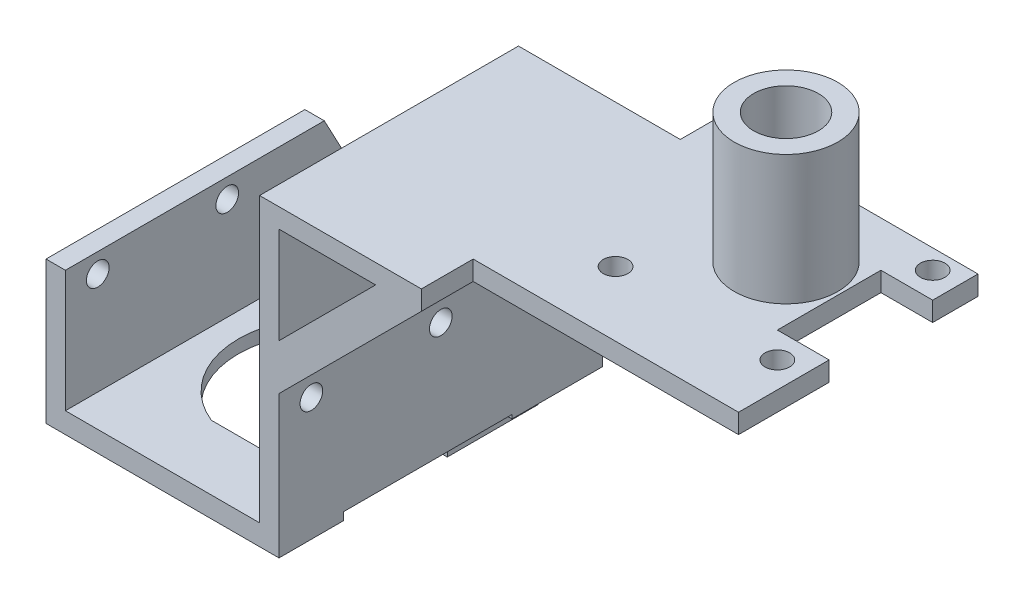
SolidWorks part; units mm, degrees
material "1060 合金"
ref_plane "前视基准面" through (0, 0, 0) normal (0, 0, 1) x (1, 0, 0)
ref_plane "上视基准面" through (0, 0, 0) normal (0, 1, 0) x (1, 0, 0)
ref_plane "右视基准面" through (0, 0, 0) normal (1, 0, 0) x (0, 0, -1)
sketch "草图1" plane through (0, 0, 0) normal (0, 1, 0) x (1, 0, 0)
  line L1 (-18, 20) -> (18, 20)
  line L2 (-18, 20) -> (-18, -20)
  line L3 (-18, -20) -> (18, -20)
  line L4 (18, 20) -> (18, -20)
  line L5 (-18, 20) -> (18, -20) construction
  line L6 (-18, -20) -> (18, 20) construction
  point P0 (0, 0)
  dimension "D1" = 40
  dimension "D2" = 36
extrude "凸台-拉伸1" add sketch "草图1" along normal blind 3
ref_plane "基准面1" through (0, 3, 0) normal (0, 1, 0) x (1, 0, 0)
sketch "草图2" plane through (0, 3, 0) normal (0, 1, 0) x (1, 0, 0)
  line L0 (-18, -20) -> (18, -20) construction
  line L1 (-18, 20) -> (-15, 20)
  line L2 (-18, 20) -> (-18, -20)
  line L3 (-18, -20) -> (-15, -20)
  line L4 (-15, 20) -> (-15, -20)
  line L6 (18, 20) -> (15, 20)
  line L7 (18, 20) -> (18, -20)
  line L8 (18, -20) -> (15, -20)
  line L9 (15, 20) -> (15, -20)
  dimension "D1" = 3
  dimension "D2" = 3
extrude "凸台-拉伸2" add sketch "草图2" along normal blind 18.8
ref_plane "基准面2" through (0, 0, 0) normal (0, -1, 0) x (-1, 0, 0)
sketch "草图3" plane through (0, 0, 0) normal (0, -1, 0) x (-1, 0, 0)
  circle A0 centre (-2.75, 3) radius 14
  dimension "D1" = 28
extrude "切除-拉伸1" cut sketch "草图3" against normal blind 9
ref_plane "基准面3" through (0, 0, 20) normal (0, 0, 1) x (1, 0, 0)
sketch "草图4" plane through (0, 0, 20) normal (0, 0, 1) x (1, 0, 0)
  line L0 (18, 21.8) -> (18, 0) construction
  line L1 (-18, 0) -> (18, 0)
  line L2 (-18, 0) -> (-18, 3)
  line L3 (-18, 3) -> (18, 3)
  line L4 (18, 0) -> (18, 3)
  line L5 (16.5, 3) -> (-16.5, 3) construction
extrude "凸台-拉伸3" add sketch "草图4" along normal blind 10
sketch "草图6" plane through (0, 0, 0) normal (0, -1, 0) x (-1, 0, 0)
  circle A0 centre (-2.75, -16.15) radius 2.7
  dimension "D2" = 5.4
  dimension "D1" = 19.15
extrude "切除-拉伸3" cut sketch "草图6" against normal blind 10
ref_plane "基准面4" through (-18, 0, 0) normal (-1, 0, 0) x (0, 0, 1)
sketch "草图7" plane through (-18, 0, 0) normal (-1, 0, 0) x (0, 0, 1)
  line L0 (20, -1.65) -> (20, 1.65) construction
  line L2 (-20, 21.8) -> (20, 21.8) construction
  circle A0 centre (15, 18.8) radius 1.75
  circle A1 centre (-5, 18.8) radius 1.75
  dimension "D1" = 3.5
  dimension "D2" = 3.5
  dimension "D3" = 5
  dimension "D4" = 3
  dimension "D5" = 3
  dimension "D6" = 20
extrude "切除-拉伸4" cut sketch "草图7" against normal through all
ref_plane "基准面5" through (0, 0, 0) normal (0, -1, 0) x (-1, 0, 0)
ref_plane "基准面6" through (0, 0, 30) normal (0, 0, 1) x (1, 0, 0)
sketch "草图9" plane through (0, 0, 30) normal (0, 0, 1) x (1, 0, 0)
  line L0 (-18, 13.365) -> (-18, -13.365) construction
  line L1 (-18, 0) -> (-15, 0)
  line L2 (-18, 0) -> (-18, -9.3)
  line L3 (-18, -9.3) -> (-15, -9.3)
  line L4 (-15, 0) -> (-15, -9.3)
  line L5 (-18, 3) -> (-18, 0) construction
  line L6 (-55, 0) -> (55, 0) construction
  line L7 (-15, -9.3) -> (10, -9.3)
  line L8 (-15, -9.3) -> (-15, -6.3)
  line L9 (-15, -6.3) -> (10, -6.3)
  line L10 (10, -9.3) -> (10, -6.3)
  dimension "D1" = 3
  dimension "D2" = 9.3
  dimension "D3" = 3
  dimension "D4" = 25
extrude "凸台-拉伸4" add sketch "草图9" against normal blind 20 contours L7 L10 L9 L4 | L4 L1 L2 L3
chamfer "倒角1" distance 5 angle 45 1 edges at (10, -7.8, 30)
sketch "草图10" plane through (0, 0, 0) normal (0, 1, 0) x (1, 0, 0)
  circle A0 centre (2.75, -16.15) radius 2.7
extrude "切除-拉伸5" cut sketch "草图10" against normal blind 30
sketch "草图11" plane through (-18, 0, 0) normal (-1, 0, 0) x (0, 0, 1)
  line L1 (40.054, -18.0711) -> (0, -18.0711)
  line L2 (40.054, -18.0711) -> (40.054, 0)
  line L3 (40.054, 0) -> (0, 0)
  line L4 (0, -18.0711) -> (0, 0)
extrude "切除-拉伸6" cut sketch "草图11" against normal through all
sketch "草图12" plane through (0, 0, 0) normal (0, -1, 0) x (-1, 0, 0)
  line L0 (18, 20) -> (18, -30) construction
  line L1 (-18, -30) -> (18, -30)
  line L2 (-18, -30) -> (-18, -10)
  line L3 (-18, -10) -> (18, -10)
  line L4 (18, -30) -> (18, -10)
  circle A0 centre (-2.75, -16.15) radius 2.7
  dimension "D1" = 20
extrude "凸台-拉伸5" add sketch "草图12" along normal blind 2.5
sketch "草图13" plane through (0, 0, 0) normal (0, -1, 0) x (-1, 0, 0)
  line L1 (-30.9744, -10) -> (31.1483, -10)
  line L2 (-30.9744, -10) -> (-30.9744, 25.5614)
  line L3 (-30.9744, 25.5614) -> (31.1483, 25.5614)
  line L4 (31.1483, -10) -> (31.1483, 25.5614)
extrude "切除-拉伸7" cut sketch "草图13" against normal blind 1
ref_plane "基准面7" through (18, 0, 0) normal (1, 0, 0) x (0, 0, -1)
ref_plane "基准面8" through (0, 0, 20) normal (0, 0, 1) x (1, 0, 0)
sketch "草图16" plane through (0, 0, 20) normal (0, 0, 1) x (1, 0, 0)
  line L0 (18, -13.365) -> (18, 13.365) construction
  line L1 (15, 21.8) -> (18, 21.8)
  line L2 (15, 21.8) -> (15, 46.8)
  line L3 (15, 46.8) -> (18, 46.8)
  line L4 (18, 21.8) -> (18, 46.8)
  line L6 (18, 46.8) -> (78, 46.8)
  line L7 (18, 46.8) -> (18, 43.8)
  line L8 (18, 43.8) -> (78, 43.8)
  line L9 (78, 46.8) -> (78, 43.8)
  dimension "D1" = 25
  dimension "D2" = 60
  dimension "D3" = 3
extrude "凸台-拉伸7" add sketch "草图16" against normal blind 65 contours L9 L6 L4 L8 | L1 L4 L3 L2
ref_plane "基准面9" through (0, 9, 0) normal (0, -1, 0) x (-1, 0, 0)
sketch "草图17" plane through (0, 9, 0) normal (0, -1, 0) x (-1, 0, 0)
  line L0 (-15, 9.7777) -> (-15, -3.7777)
  circle A0 centre (-2.75, 3) radius 14
extrude "凸台-拉伸8" add sketch "草图17" along normal up to surface (8 mm away) contours L0 A0
ref_plane "基准面10" through (0, 46.8, 0) normal (0, 1, 0) x (1, 0, 0)
sketch "草图18" plane through (0, 46.8, 0) normal (0, 1, 0) x (1, 0, 0)
  line L0 (78, 45) -> (78, -20) construction
  line L1 (47.75, 25.75) -> (74.25, 25.75) construction
  line L2 (47.75, 25.75) -> (47.75, -0.75) construction
  line L3 (47.75, -0.75) -> (74.25, -0.75) construction
  line L4 (74.25, 25.75) -> (74.25, -0.75) construction
  line L5 (47.75, 25.75) -> (74.25, -0.75) construction
  line L6 (47.75, -0.75) -> (74.25, 25.75) construction
  line L10 (47.75, 12.5) -> (74.25, 12.5) construction
  line L11 (52, -0.75) -> (70, -0.75) construction
  line L12 (52, -2.75) -> (70, -2.75)
  line L13 (52, 1.25) -> (70, 1.25)
  line L14 (15, 12.5) -> (78, 12.5) construction
  line L15 (15, 45) -> (15, -20) construction
  circle A2 centre (74.25, -0.75) radius 1.15
  circle A3 centre (47.75, -0.75) radius 1.15
  circle A4 centre (61, 12.5) radius 10
  arc A7 (52, -2.75) -> (52, 1.25) centre (52, -0.75) cw
  arc A8 (70, 1.25) -> (70, -2.75) centre (70, -0.75) cw
  point P0 (61, 12.5)
  point P24 (61, -0.75)
  dimension "D3" = 13.25
  dimension "D4" = 2
  dimension "D5" = 2.3
  dimension "D6" = 2.3
  dimension "D8" = 20
  dimension "D1" = 26.5
  dimension "D2" = 26.5
  dimension "D7" = 17
  dimension "D9" = 18
ref_plane "基准面11" through (0, -2.5, 0) normal (0, -1, 0) x (-1, 0, 0)
sketch "草图19" plane through (0, -2.5, 0) normal (0, -1, 0) x (-1, 0, 0)
  line L1 (-57.3424, 35.7643) -> (67.8869, 35.7643)
  line L2 (-57.3424, 35.7643) -> (-57.3424, -68.1586)
  line L3 (-57.3424, -68.1586) -> (67.8869, -68.1586)
  line L4 (67.8869, 35.7643) -> (67.8869, -68.1586)
extrude "切除-拉伸9" cut sketch "草图19" against normal blind 0.5
ref_plane "基准面12" through (0, -2, 0) normal (0, -1, 0) x (-1, 0, 0)
sketch "草图20" plane through (0, -2, 0) normal (0, -1, 0) x (-1, 0, 0)
  line L1 (-74.5179, 37.5036) -> (80.2794, 37.5036)
  line L2 (-74.5179, 37.5036) -> (-74.5179, -52.9398)
  line L3 (-74.5179, -52.9398) -> (80.2794, -52.9398)
  line L4 (80.2794, 37.5036) -> (80.2794, -52.9398)
extrude "切除-拉伸10" cut sketch "草图20" against normal blind 1.8
ref_plane "基准面13" through (0, 0, 0) normal (0, 1, 0) x (1, 0, 0)
sketch "草图21" plane through (0, 0, 0) normal (0, 1, 0) x (1, 0, 0)
  line L1 (-2.4461, -10) -> (8.7096, -10)
  line L2 (-2.4461, -10) -> (-2.4461, -12.6038)
  line L3 (-2.4461, -12.6038) -> (8.7096, -12.6038)
  line L4 (8.7096, -10) -> (8.7096, -12.6038)
extrude "凸台-拉伸9" add sketch "草图21" along normal up to surface (3 mm away) up to face at (2.75, 3, 18.85)
ref_plane "基准面14" through (0, 0, -20) normal (0, 0, -1) x (-1, 0, 0)
sketch "草图22" plane through (0, 0, -20) normal (0, 0, -1) x (-1, 0, 0)
  line L0 (18, -17.325) -> (18, 17.325) construction
  line L1 (18, 3) -> (-18, 3)
  line L2 (18, 3) -> (18, -0.2)
  line L3 (18, -0.2) -> (-18, -0.2)
  line L4 (-18, 3) -> (-18, -0.2)
  line L5 (18, 3) -> (18, -0.2) construction
  line L6 (-18, 21.8) -> (-18, 1) construction
  line L7 (-15, 3) -> (15, 3) construction
  dimension "D1" = 3.2
extrude "凸台-拉伸10" add sketch "草图22" along normal blind 10 and the other way blind 4
sketch "草图23" plane through (0, 9, 0) normal (0, -1, 0) x (-1, 0, 0)
  circle A0 centre (-2.75, 22.15) radius 1.75
  arc A1 (2.4461, -10) -> (2.4462, 16) centre (-2.75, 3) ccw construction
  dimension "D1" = 19.15
  dimension "D2" = 3.5
extrude "切除-拉伸12" cut sketch "草图23" along normal blind 10
sketch "草图26" plane through (0, 3, 0) normal (0, 1, 0) x (1, 0, 0)
  line L1 (-3.0023, -13.2404) -> (9.8436, -13.2404)
  line L2 (-3.0023, -13.2404) -> (-3.0023, -20.6177)
  line L3 (-3.0023, -20.6177) -> (9.8436, -20.6177)
  line L4 (9.8436, -13.2404) -> (9.8436, -20.6177)
extrude "凸台-拉伸11" add sketch "草图26" against normal through all
sketch "草图27" plane through (0, 0, 30) normal (0, 0, 1) x (1, 0, 0)
  line L1 (-53.429, 28.6042) -> (62.9951, 28.6042)
  line L2 (-53.429, 28.6042) -> (-53.429, -33.9017)
  line L3 (-53.429, -33.9017) -> (62.9951, -33.9017)
  line L4 (62.9951, 28.6042) -> (62.9951, -33.9017)
extrude "切除-拉伸13" cut sketch "草图27" against normal blind 10
ref_plane "基准面16" through (0, 46.8, 0) normal (0, 1, 0) x (1, 0, 0)
sketch "草图29" plane through (0, 46.8, 0) normal (0, 1, 0) x (1, 0, 0)
  line L0 (-12.1, -20) -> (12.1, -20) construction
  line L1 (88.2149, 37) -> (-1.5762, 37)
  line L2 (88.2149, 37) -> (88.2149, 49.2847)
  line L3 (88.2149, 49.2847) -> (-1.5762, 49.2847)
  line L4 (-1.5762, 37) -> (-1.5762, 49.2847)
  line L5 (110.1735, -41.7854) -> (2.772, -41.7854)
  line L6 (110.1735, -41.7854) -> (110.1735, -12)
  line L7 (110.1735, -12) -> (2.772, -12)
  line L8 (2.772, -41.7854) -> (2.772, -12)
  line L9 (15, 45) -> (78, 45) construction
  dimension "D1" = 8
  dimension "D2" = 8
extrude "切除-拉伸14" cut sketch "草图29" against normal blind 25
ref_plane "基准面17" through (0, 0, -20) normal (0, 0, -1) x (-1, 0, 0)
sketch "草图30" plane through (0, 0, -20) normal (0, 0, -1) x (-1, 0, 0)
  line L0 (19.8, 3) -> (-19.8, 3) construction
  line L1 (-18, 21.8) -> (-15, 21.8)
  line L2 (-18, 21.8) -> (-18, 3)
  line L3 (-18, 3) -> (-15, 3)
  line L4 (-15, 21.8) -> (-15, 3)
  line L5 (18, 3) -> (-18, 3) construction
extrude "凸台-拉伸12" add sketch "草图30" along normal up to surface (17 mm away) up to face at (37, 37.4667, -37)
ref_plane "基准面18" through (0, -0.2, 0) normal (0, -1, 0) x (-1, 0, 0)
sketch "草图31" plane through (0, -0.2, 0) normal (0, -1, 0) x (-1, 0, 0)
  line L1 (-43.7541, 52.6137) -> (37.0144, 52.6137)
  line L2 (-43.7541, 52.6137) -> (-43.7541, 6.8485)
  line L3 (-43.7541, 6.8485) -> (37.0144, 6.8485)
  line L4 (37.0144, 52.6137) -> (37.0144, 6.8485)
extrude "切除-拉伸15" cut sketch "草图31" against normal blind 0.6
ref_plane "基准面19" through (0, 0, -30) normal (0, 0, -1) x (-1, 0, 0)
sketch "草图32" plane through (0, 0, -30) normal (0, 0, -1) x (-1, 0, 0)
  line L0 (15, 21.8) -> (15, 3) construction
  line L1 (15, 3) -> (18, 3)
  line L2 (15, 3) -> (15, -9.7)
  line L3 (15, -9.7) -> (18, -9.7)
  line L4 (18, 3) -> (18, -9.7)
  line L5 (15, 3) -> (18, 3) construction
  line L6 (18, -17.325) -> (18, 17.325) construction
  line L7 (-7.7, -0.2) -> (7.7, -0.2) construction
  line L8 (18, -9.7) -> (-8, -9.7)
  line L9 (18, -9.7) -> (18, -6.9)
  line L10 (18, -6.9) -> (-8, -6.9)
  line L11 (-8, -9.7) -> (-8, -6.9)
  dimension "D1" = 6.7
  dimension "D2" = 26
  dimension "D3" = 12.7
extrude "凸台-拉伸13" add sketch "草图32" against normal up to surface (14 mm away) contours L11 L8 L2 L10 | L10 L4 L1 L2 | L4 L10 L2 L3 up to face at (1.375, 1.35, -16)
sketch "草图34" plane through (0, 3, 0) normal (0, 1, 0) x (1, 0, 0)
  circle A0 centre (2.75, 22.15) radius 2.2
  dimension "D1" = 4.4
extrude "切除-拉伸17" cut sketch "草图34" against normal through all
ref_plane "基准面20" through (0, 0, -37) normal (0, 0, -1) x (-1, 0, 0)
sketch "草图35" plane through (0, 0, -37) normal (0, 0, -1) x (-1, 0, 0)
  line L1 (69.9523, -61.8537) -> (-98.7594, -61.8537)
  line L2 (69.9523, -61.8537) -> (69.9523, 67.0716)
  line L3 (69.9523, 67.0716) -> (-98.7594, 67.0716)
  line L4 (-98.7594, -61.8537) -> (-98.7594, 67.0716)
extrude "切除-拉伸18" cut sketch "草图35" against normal up to surface (7 mm away) up to face at (0.1111, -2.6, -30)
sketch "草图36" plane through (0, 46.8, 0) normal (0, 1, 0) x (1, 0, 0)
  line L0 (78, 30) -> (15, 30) construction
  line L1 (41, 20) -> (10.219, 20)
  line L2 (41, 20) -> (41, 40.3835)
  line L3 (41, 40.3835) -> (10.219, 40.3835)
  line L4 (10.219, 20) -> (10.219, 40.3835)
  line L5 (15, 30) -> (15, 9.7777) construction
  dimension "D1" = 10
  dimension "D2" = 26
extrude "切除-拉伸19" cut sketch "草图36" against normal up to surface (43.8 mm away) up to face at (2.75, 3, -19.95)
sketch "草图38" plane through (0, 46.8, 0) normal (0, 1, 0) x (1, 0, 0)
  line L0 (78, 30) -> (78, -12) construction
  line L1 (41, 30) -> (78, 30)
  line L2 (41, 30) -> (41, 25)
  line L3 (41, 25) -> (78, 25)
  line L4 (78, 30) -> (78, 25)
  dimension "D1" = 5
extrude "切除-拉伸20" cut sketch "草图38" against normal blind 10
sketch "草图39" plane through (0, 46.8, 0) normal (0, 1, 0) x (1, 0, 0)
  line L1 (54.75, 2) -> (67.25, 2)
  line L2 (54.75, 2) -> (54.75, 23)
  line L3 (54.75, 23) -> (67.25, 23)
  line L4 (67.25, 2) -> (67.25, 23)
  line L5 (54.75, 2) -> (67.25, 23) construction
  line L6 (54.75, 23) -> (67.25, 2) construction
  point P0 (61, 12.5)
  dimension "D1" = 21
  dimension "D2" = 12.5
sketch "草图40" plane through (0, 46.8, 0) normal (0, 1, 0) x (1, 0, 0)
  point P0 (54.75, 23)
  point P3 (67.25, 23)
  point P6 (54.75, 2)
  point P9 (67.25, 2)
sketch "草图44" plane through (0, 46.8, 0) normal (0, 1, 0) x (1, 0, 0)
  line L1 (51, 6.5) -> (71, 6.5)
  line L2 (51, 6.5) -> (51, 18.5)
  line L3 (51, 18.5) -> (71, 18.5)
  line L4 (71, 6.5) -> (71, 18.5)
  line L5 (51, 6.5) -> (71, 18.5) construction
  line L6 (51, 18.5) -> (71, 6.5) construction
  line L8 (71, 18.5) -> (61, 18.5)
  line L9 (71, 18.5) -> (71, 23.5)
  line L10 (71, 23.5) -> (61, 23.5)
  line L11 (61, 18.5) -> (61, 23.5)
  point P0 (61, 12.5)
  dimension "D1" = 12
  dimension "D2" = 20
  dimension "D3" = 10
  dimension "D4" = 5
sketch "草图45" plane through (0, 0, -25) normal (0, 0, -1) x (-1, 0, 0)
  line L0 (-15, 46.8) -> (-78, 46.8) construction
  line L1 (-78, 46.8) -> (-41, 46.8)
  line L2 (-78, 46.8) -> (-78, 43.8)
  line L3 (-78, 43.8) -> (-41, 43.8)
  line L4 (-41, 46.8) -> (-41, 43.8)
  line L5 (-78, 43.8) -> (-78, 46.8) construction
extrude "凸台-拉伸14" add sketch "草图45" along normal blind 3
sketch "草图46" plane through (0, 46.8, 0) normal (0, 1, 0) x (1, 0, 0)
  line L0 (78, 28) -> (78, -12) construction
  line L1 (15, -12) -> (78, -12) construction
  line L2 (52, 22) -> (77, 22)
  line L3 (52, 22) -> (52, -2)
  line L4 (52, -2) -> (77, -2)
  line L5 (77, 22) -> (77, -2)
  line L6 (52, 22) -> (77, -2) construction
  line L7 (52, -2) -> (77, 22) construction
  point P4 (64.5, 10)
  dimension "D1" = 25
  dimension "D2" = 24
  dimension "D3" = 13.5
  dimension "D4" = 22
sketch "草图47" plane through (0, 46.8, 0) normal (0, 1, 0) x (1, 0, 0)
  point P0 (52, 22)
  point P3 (52, -2)
  point P6 (77, 22)
  point P9 (77, -2)
hole_wizard "孔1" positions "草图47" profile "草图48" legacy end condition up to next
sketch "草图48" plane through (52, 46.8, -22) normal (1, 0, 0) x (0, 0, 1)
  line L0 (0, 0) -> (0, 3)
  line L1 (0, 3) -> (1.9, 3)
  line L2 (1.9, 3) -> (1.9, 0)
  line L3 (1.9, 0) -> (0, 0)
  line L4 (0, 110) -> (0, -10) construction
  dimension "直径" = 3.8
  dimension "深度" = 3
sketch "草图51" plane through (0, 46.8, 0) normal (0, 1, 0) x (1, 0, 0)
  line L0 (78, 28) -> (78, 23.6155) construction
  line L1 (41, 28) -> (78, 28)
  line L2 (41, 28) -> (41, 20)
  line L3 (41, 20) -> (78, 20)
  line L4 (78, 28) -> (78, 20)
  line L5 (1.65, 20) -> (-1.65, 20) construction
extrude "切除-拉伸21" cut sketch "草图51" against normal blind 10
sketch "草图52" plane through (-18, 0, 0) normal (-1, 0, 0) x (0, 0, 1)
  line L0 (-30, 3) -> (-20, 21.8)
  line L1 (-30, 6.985) -> (-30, -6.985) construction
  line L2 (19.8, 3) -> (-19.8, 3) construction
  line L3 (-20, 1.65) -> (-20, -1.65) construction
  line L4 (-20, 46.8) -> (-20, 3) construction
  line L5 (-20, 21.8) -> (-20, 3)
  line L6 (-20, 3) -> (-30, 3)
extrude "凸台-拉伸15" add sketch "草图52" against normal blind 3
sketch "草图54" plane through (18, 0, 0) normal (1, 0, 0) x (0, 0, -1)
  line L0 (30, 3) -> (20, 3)
  line L1 (19.8, 3) -> (-19.8, 3) construction
  line L2 (20, 21.8) -> (30, 3) construction
  line L3 (20, -1.65) -> (20, 1.65) construction
  line L4 (20, 3) -> (20, 23.4)
  line L5 (20, 3) -> (20, 43.8) construction
  line L6 (20, 23.4) -> (30, 3)
extrude "凸台-拉伸16" add sketch "草图54" against normal blind 3
sketch "草图55" plane through (0, 0, 12) normal (0, 0, 1) x (1, 0, 0)
  line L0 (18, 21.8) -> (40, 43.8)
  line L1 (18, 43.8) -> (78, 43.8) construction
  line L2 (40, 43.8) -> (18, 43.8)
  line L3 (18, 43.8) -> (18, 21.8)
  line L4 (18, 21.8) -> (15, 21.8)
  line L5 (15, 21.8) -> (15, 3) construction
  line L6 (15, 21.8) -> (18, 21.8) construction
  line L7 (15, 21.8) -> (15, 46.8)
  line L8 (15, 46.8) -> (78, 46.8) construction
  line L9 (15, 21.8) -> (15, 46.8) construction
  line L10 (15, 46.8) -> (40, 46.8)
  line L11 (40, 46.8) -> (40, 43.8)
  line L12 (18, 28.8711) -> (32.9289, 43.8)
  line M5 (15, 21.8) -> (18, 21.8)
  line M6 (18, 21.8) -> (18, 43.8)
  line M7 (18, 43.8) -> (78, 43.8)
  line M9 (78, 46.8) -> (15, 46.8)
  line M10 (15, 46.8) -> (15, 21.8)
  dimension "D1" = 45
  dimension "D2" = 5
extrude "凸台-拉伸17" add sketch "草图55" along normal up to surface (8 mm away) contours L11 L3 L2 M9 M10 M5 M6 M7 | L12 L0 L2 M6 up to face at (0, 11.6, 20)
ref_plane "基准面21" through (0, 0, -4) normal (0, 0, 1) x (1, 0, 0)
sketch "草图56" plane through (0, 0, -4) normal (0, 0, 1) x (1, 0, 0)
  line L0 (18, 21.8) -> (40, 43.8)
  line L1 (40, 43.8) -> (32.9289, 43.8)
  line L2 (32.9289, 43.8) -> (18, 28.8711)
  line L3 (18, 28.8711) -> (18, 21.8)
extrude "凸台-拉伸18" add sketch "草图56" along normal mid plane 3
sketch "草图58" plane through (0, 0, -30) normal (0, 0, -1) x (-1, 0, 0)
  line L0 (15, -6.9) -> (-8, -6.9) construction
  line L1 (15, 0.4) -> (10, 0.4)
  line L2 (15, 0.4) -> (15, -6.9)
  line L3 (15, -6.9) -> (10, -6.9)
  line L4 (10, 0.4) -> (10, -6.9)
  dimension "D1" = 5
extrude "凸台-拉伸19" add sketch "草图58" against normal blind 3
sketch "草图59" plane through (0, 46.8, 0) normal (0, 1, 0) x (1, 0, 0)
  line L0 (1.65, 20) -> (-1.65, 20) construction
  line L1 (78, 20) -> (40, 20)
  line L2 (78, 20) -> (78, 25)
  line L3 (78, 25) -> (40, 25)
  line L4 (40, 20) -> (40, 25)
  line L5 (78, 20) -> (78, -0.3845) construction
  line L6 (40, -20) -> (40, -12) construction
  dimension "D1" = 5
extrude "凸台-拉伸20" add sketch "草图59" against normal blind 3
sketch "草图60" plane through (0, 46.8, 0) normal (0, 1, 0) x (1, 0, 0)
  point P0 (52, 22)
  point P3 (77, 22)
hole_wizard "孔2" positions "草图60" profile "草图61" legacy end condition up to next
sketch "草图61" plane through (52, 46.8, -22) normal (1, 0, 0) x (0, 0, 1)
  line L0 (0, 0) -> (0, 3)
  line L1 (0, 3) -> (1.9, 3)
  line L2 (1.9, 3) -> (1.9, 0)
  line L3 (1.9, 0) -> (0, 0)
  line L4 (0, 110) -> (0, -10) construction
  dimension "直径" = 3.8
  dimension "深度" = 3
sketch "草图62" plane through (78, 0, 0) normal (1, 0, 0) x (0, 0, -1)
  line L0 (25.75, 46.8) -> (-0.75, 46.8) construction
  line L1 (-12, 43.8) -> (25, 43.8)
  line L2 (-12, 43.8) -> (-12, 46.8)
  line L3 (-12, 46.8) -> (25, 46.8)
  line L4 (25, 43.8) -> (25, 46.8)
  line L5 (25.75, 46.8) -> (-0.75, 46.8) construction
extrude "凸台-拉伸21" add sketch "草图62" along normal blind 3
sketch "草图63" plane through (0, 46.8, 0) normal (0, 1, 0) x (1, 0, 0)
  point P0 (77, -2)
  point P3 (77, 22)
hole_wizard "孔3" positions "草图63" profile "草图64" legacy end condition up to next
sketch "草图64" plane through (77, 46.8, 2) normal (1, 0, 0) x (0, 0, 1)
  line L0 (0, 0) -> (0, 56.5)
  line L1 (0, 56.5) -> (1.9, 56.5)
  line L2 (1.9, 56.5) -> (1.9, 0)
  line L3 (1.9, 0) -> (0, 0)
  line L4 (0, 110) -> (0, -10) construction
  dimension "直径" = 3.8
  dimension "深度" = 56.5
sketch "草图65" plane through (0, 46.8, 0) normal (0, 1, 0) x (1, 0, 0)
  line L0 (77, 22) -> (77, -2) construction
  line L1 (73, 18) -> (81, 18)
  line L2 (73, 18) -> (73, 2)
  line L3 (73, 2) -> (81, 2)
  line L4 (81, 18) -> (81, 2)
  line L5 (73, 18) -> (81, 2) construction
  line L6 (73, 2) -> (81, 18) construction
  line L7 (81, 25) -> (81, -12) construction
  point P0 (77, 10)
  dimension "D1" = 16
extrude "切除-拉伸22" cut sketch "草图65" against normal blind 10
sketch "草图66" plane through (0, 46.8, 0) normal (0, 1, 0) x (1, 0, 0)
  line L0 (15, 30) -> (15, 9.7777) construction
  line L1 (15, 19.8889) -> (18, 19.8889)
  line L2 (15, 19.8889) -> (15, -20)
  line L3 (15, -20) -> (18, -20)
  line L4 (18, 19.8889) -> (18, -20)
  line L5 (-31.9, -20) -> (31.9, -20) construction
  dimension "D1" = 3
sketch "草图73" plane through (0, 46.8, 0) normal (0, 1, 0) x (1, 0, 0)
  line L0 (81, 25) -> (40, 25) construction
  line L1 (81, 25) -> (81, 18) construction
  circle A0 centre (64.5211, 11.8182) radius 8
  point P0 (64.5211, 11.8182)
  dimension "D3" = 16
  dimension "D1" = 13.1818
  dimension "D2" = 16.4789
extrude "凸台-拉伸22" add sketch "草图73" along normal blind 20
sketch "草图74" plane through (0, 66.8, 0) normal (0, 1, 0) x (1, 0, 0)
  circle A0 centre (64.5211, 11.8182) radius 5
  dimension "D1" = 10
extrude "切除-拉伸23" cut sketch "草图74" against normal blind 20 contours A0
hole_wizard "孔4" positions "草图75" profile "草图76" legacy end condition through all
sketch "草图75" plane through (0, 46.8, 0) normal (0, 1, 0) x (1, 0, 0)
  point P0 (64.5211, 11.8182)
sketch "草图76" plane through (64.5211, 46.8, -11.8182) normal (1, 0, 0) x (0, 0, 1)
  line L0 (0, 0) -> (0, 56.5)
  line L1 (0, 56.5) -> (4, 56.5)
  line L2 (4, 56.5) -> (4, 0)
  line L3 (4, 0) -> (0, 0)
  line L4 (0, 110) -> (0, -10) construction
  dimension "直径" = 8
  dimension "深度" = 56.5
